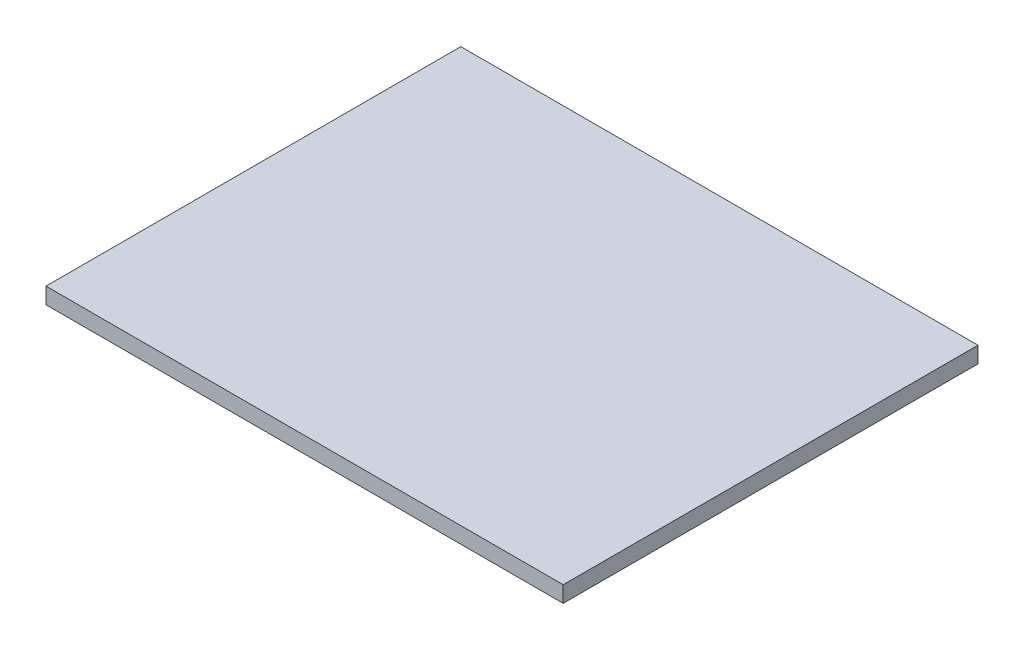
SolidWorks part; units mm, degrees
material "6061 Alloy"
ref_plane "Front Plane" through (0, 0, 0) normal (0, 0, 1) x (1, 0, 0)
ref_plane "Top Plane" through (0, 0, 0) normal (0, 1, 0) x (1, 0, 0)
ref_plane "Right Plane" through (0, 0, 0) normal (1, 0, 0) x (0, 0, -1)
sketch "Sketch1" plane through (0, 0, 0) normal (0, 1, 0) x (1, 0, 0)
  line L0 (0, 0) -> (-0.762, 0) construction
  line L1 (0, 0) -> (22.86, 0)
  line L2 (0, 0) -> (0, 18.034)
  line L3 (0, 18.034) -> (22.86, 18.034)
  line L4 (22.86, 0) -> (22.86, 18.034)
  line L5 (-0.762, -0.762) -> (23.622, -0.762)
  line L6 (-0.762, -0.762) -> (-0.762, 18.796)
  line L7 (-0.762, 18.796) -> (23.622, 18.796)
  line L8 (23.622, -0.762) -> (23.622, 18.796)
  line L9 (0, 0) -> (0, -0.762) construction
  line L10 (0, 0) -> (22.86, 18.034) construction
  line L11 (23.622, -0.762) -> (-0.762, 18.796) construction
  line L13 (-0.762, -0.762) -> (23.622, -0.762)
  line L14 (-0.762, -0.762) -> (-0.762, 18.796)
  line L15 (-0.762, 18.796) -> (23.622, 18.796)
  line L16 (23.622, -0.762) -> (23.622, 18.796)
  point P9 (11.43, 9.017)
  point P12 (11.43, 9.017)
  dimension "D1" = 18.034
  dimension "D2" = 22.86
  dimension "D3" = 0.762
sketch "Sketch4" plane through (0, 0, 0) normal (0, 1, 0) x (1, 0, 0)
  line L1 (-0.762, -0.762) -> (23.622, -0.762)
  line L2 (-0.762, -0.762) -> (-0.762, 18.796)
  line L3 (-0.762, 18.796) -> (23.622, 18.796)
  line L4 (23.622, -0.762) -> (23.622, 18.796)
extrude "Boss-Extrude1" add sketch "Sketch4" along normal blind 0.762
sketch "Sketch6" plane through (0, 0, 0) normal (0, -1, 0) x (1, 0, 0)
  line L0 (0, 0) -> (22.86, 0)
  line L1 (22.86, 0) -> (22.86, -18.034)
  line L2 (22.86, -18.034) -> (0, -18.034)
  line L3 (0, 0) -> (0, -5.842)
  line L4 (0.762, -17.272) -> (22.098, -17.272)
  line L5 (22.098, -17.272) -> (22.098, -0.762)
  line L6 (22.098, -0.762) -> (0.762, -0.762)
  line L7 (0, -12.192) -> (0, -18.034)
  line L8 (22.098, -17.272) -> (22.86, -17.272) construction
  line L10 (0, -5.842) -> (0.762, -5.842)
  line L11 (0.762, -5.842) -> (0.762, -0.762)
  line L13 (0, -12.192) -> (0.762, -12.192)
  line L14 (0.762, -12.192) -> (0.762, -17.272)
  line L15 (22.098, -0.762) -> (22.098, 0) construction
  line L16 (22.098, -17.272) -> (22.098, -18.034) construction
  dimension "D1" = 0.762
  dimension "D2" = 6.35
extrude "Boss-Extrude2" add sketch "Sketch6" along normal blind 0.762
